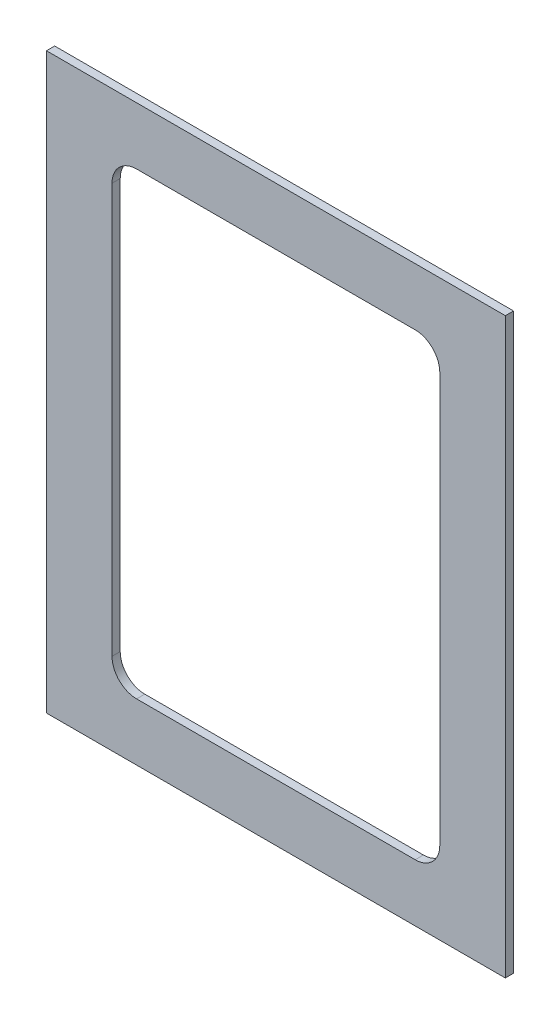
SolidWorks part; units mm, degrees
material "Alloy Steel"
ref_plane "Front Plane" through (0, 0, 0) normal (0, 0, 1) x (1, 0, 0)
ref_plane "Top Plane" through (0, 0, 0) normal (0, 1, 0) x (1, 0, 0)
ref_plane "Right Plane" through (0, 0, 0) normal (1, 0, 0) x (0, 0, -1)
sketch "Sketch1" plane through (0, 0, 0) normal (0, 0, 1) x (1, 0, 0)
  line L0 (0, 0) -> (0, 222.25) construction
  line L1 (-88.9, 0) -> (88.9, 0)
  line L2 (-88.9, 0) -> (-88.9, 222.25)
  line L3 (-88.9, 222.25) -> (88.9, 222.25)
  line L4 (88.9, 0) -> (88.9, 222.25)
  point P4 (0, 0)
  dimension "D1" = 177.8
  dimension "D2" = 222.25
extrude "Boss-Extrude1" add sketch "Sketch1" along normal blind 3.175
sketch "Sketch2" plane through (0, 0, 3.175) normal (0, 0, 1) x (1, 0, 0)
  line L0 (0, 222.25) -> (0, 0) construction
  line L1 (88.9, 222.25) -> (-88.9, 222.25) construction
  line L3 (53.975, 22.225) -> (-53.975, 22.225)
  line L4 (63.5, 31.75) -> (63.5, 190.5)
  line L5 (53.975, 200.025) -> (-53.975, 200.025)
  line L6 (-63.5, 31.75) -> (-63.5, 190.5)
  line L7 (63.5, 22.225) -> (-63.5, 200.025) construction
  line L8 (63.5, 200.025) -> (-63.5, 22.225) construction
  arc A0 (53.975, 200.025) -> (63.5, 190.5) centre (53.975, 190.5) cw
  arc A1 (-53.975, 200.025) -> (-63.5, 190.5) centre (-53.975, 190.5) ccw
  arc A2 (53.975, 22.225) -> (63.5, 31.75) centre (53.975, 31.75) ccw
  arc A3 (-63.5, 31.75) -> (-53.975, 22.225) centre (-53.975, 31.75) ccw
  point P5 (0, 111.125)
  dimension "D3" = 9.525
  dimension "D4" = 9.525
  dimension "D1" = 177.8
  dimension "D2" = 127
extrude "Cut-Extrude1" cut sketch "Sketch2" against normal through all
